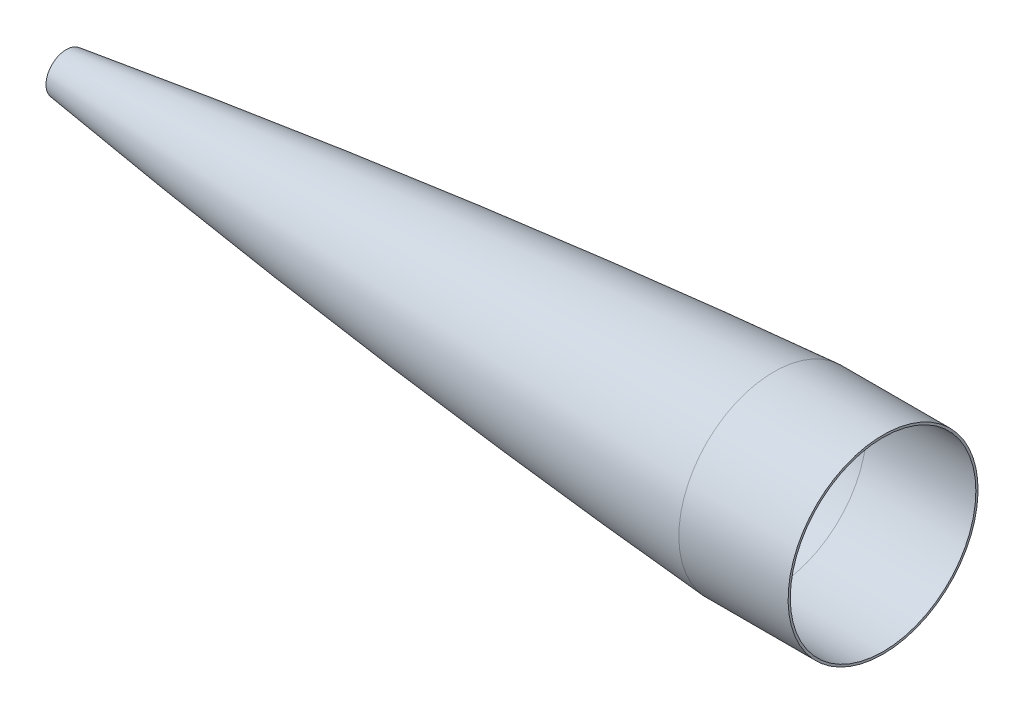
SolidWorks part; units mm, degrees
other "Markup1"
sketch "Sketch19" plane through (863.2353, 87, -87) normal (0.5122, 0.1711, -0.8417) x (-0.8532, -0.0108, -0.5214)
other "Markup2"
sketch "Sketch20" plane through (863.2353, 87, -87) normal (0.5122, 0.1711, -0.8417) x (-0.8532, -0.0108, -0.5214)
material "E-Glass Fiber"
ref_plane "Płaszczyzna przednia" through (0, 0, 0) normal (0, 0, 1) x (1, 0, 0)
ref_plane "Płaszczyzna górna" through (0, 0, 0) normal (0, 1, 0) x (1, 0, 0)
ref_plane "Płaszczyzna prawa" through (0, 0, 0) normal (1, 0, 0) x (0, 0, -1)
ref_plane "Plane1" through (0, 0, 0) normal (0, 0, -1) x (-1, 0, 0)
sketch "Sketch1" plane through (0, 0, 0) normal (0, 0, -1) x (-1, 0, 0)
  line L2 (-763.2353, 0) -> (0, 0) construction
  line L8 (-763.3824, 85) -> (-763.2353, 85)
  line L9 (-763.3824, 87) -> (-763.1616, 87)
  line L10 (0, 0) -> (18.4685, 0)
  line L11 (18.4685, 0) -> (0.2953, 1.9781)
  line L12 (-763.3824, 87) -> (-763.3824, 85)
  arc A0 (0, 0) -> (-763.2353, 85) centre (-1520.6726, -10185.346) ccw
  arc A3 (0.2953, 1.9781) -> (-763.1616, 87) centre (-1520.6726, -10185.346) ccw
  dimension "D1" = 85
  dimension "D2" = 2
revolve "Revolve1" add sketch "Sketch1" angle 360 about L2
sketch "Sketch14" plane through (0, 0, 0) normal (0, 0, -1) x (-1, 0, 0)
  line L0 (-763.2353, 85) -> (-763.2353, -85) construction
  line L1 (-763.2353, 0) -> (-863.2353, 0) construction
  line L2 (-863.2353, 0) -> (-863.2353, 85) construction
  line L9 (-763.3824, 87) -> (-763.3824, 85)
  line L10 (-763.3824, 87) -> (-863.2353, 87)
  line L11 (-863.2353, 87) -> (-863.2353, 85)
  line L12 (-763.3824, 85) -> (-863.2353, 85)
  arc A0 (-763.2353, -85) -> (0, 0) centre (-1520.6726, 10185.346) ccw construction
  dimension "D1" = 100
revolve "Revolve4" add sketch "Sketch14" angle 360 about L1
sketch "Sketch15" plane through (0, 0, 0) normal (0, 0, 1) x (1, 0, 0)
  line L0 (-17.7797, -0.075) -> (114.9971, 0)
  line L1 (-18.4685, 0) -> (-0.2953, -1.9781) construction
  line L2 (763.2353, 0) -> (0, 0) construction
  line L3 (114.9971, 0) -> (114.9971, 42.3088)
  line L4 (114.9971, 42.3088) -> (-24.7937, 42.3088)
  line L5 (-24.7937, 42.3088) -> (-24.7937, -36.0986)
  line L6 (-24.7937, -36.0986) -> (114.9971, -36.0986)
  line L7 (114.9971, -36.0986) -> (114.9971, 0)
  line L8 (114.9971, 0) -> (114.9971, -36.0986)
  dimension "D1" = 132.7768
extrude "Cut-Extrude1" cut sketch "Sketch15" along normal mid plane 100
